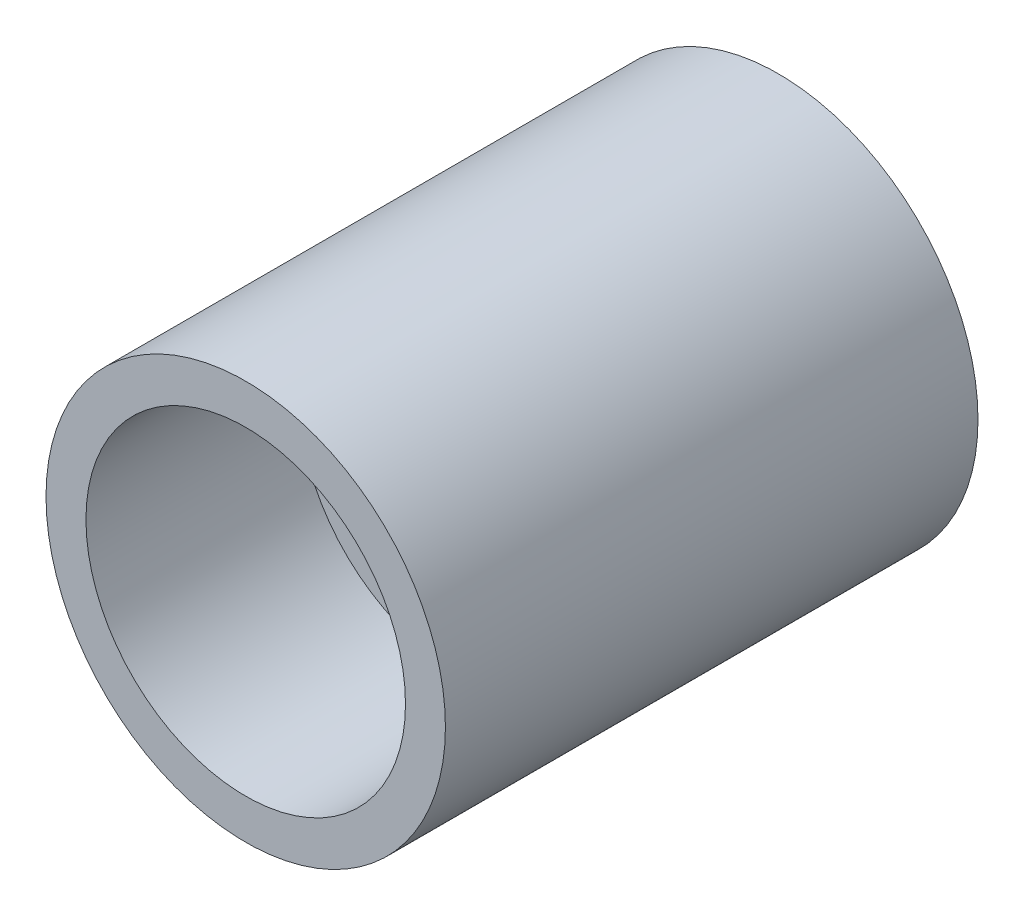
SolidWorks part; units mm, degrees
ref_plane "Front Plane" through (0, 0, 0) normal (0, 0, 1) x (1, 0, 0)
ref_plane "Top Plane" through (0, 0, 0) normal (0, 1, 0) x (1, 0, 0)
ref_plane "Right Plane" through (0, 0, 0) normal (1, 0, 0) x (0, 0, -1)
sketch "Sketch1" plane through (0, 0, 0) normal (0, 0, 1) x (1, 0, 0)
  circle A0 centre (0, 0) radius 3.75
  circle A1 centre (0, 0) radius 3
  dimension "D1" = 7.5
  dimension "D2" = 6
extrude "Boss-Extrude1" add sketch "Sketch1" along normal blind 4
sketch "Sketch2" plane through (0, 0, 0) normal (0, 0, -1) x (-1, 0, 0)
  circle A0 centre (0, 0) radius 3.75 construction
  circle A1 centre (0, 0) radius 3.75
  circle A2 centre (0, 0) radius 1
  dimension "D1" = 2
extrude "Boss-Extrude2" add sketch "Sketch2" along normal blind 6
sketch "Sketch3" plane through (0, 0, -6) normal (0, 0, -1) x (-1, 0, 0)
  circle A0 centre (0, 0) radius 2
  circle A1 centre (0, 0) radius 1 construction
  circle A2 centre (0, 0) radius 1
  dimension "D1" = 4
extrude "Boss-Extrude3" add sketch "Sketch3" along normal blind 1
